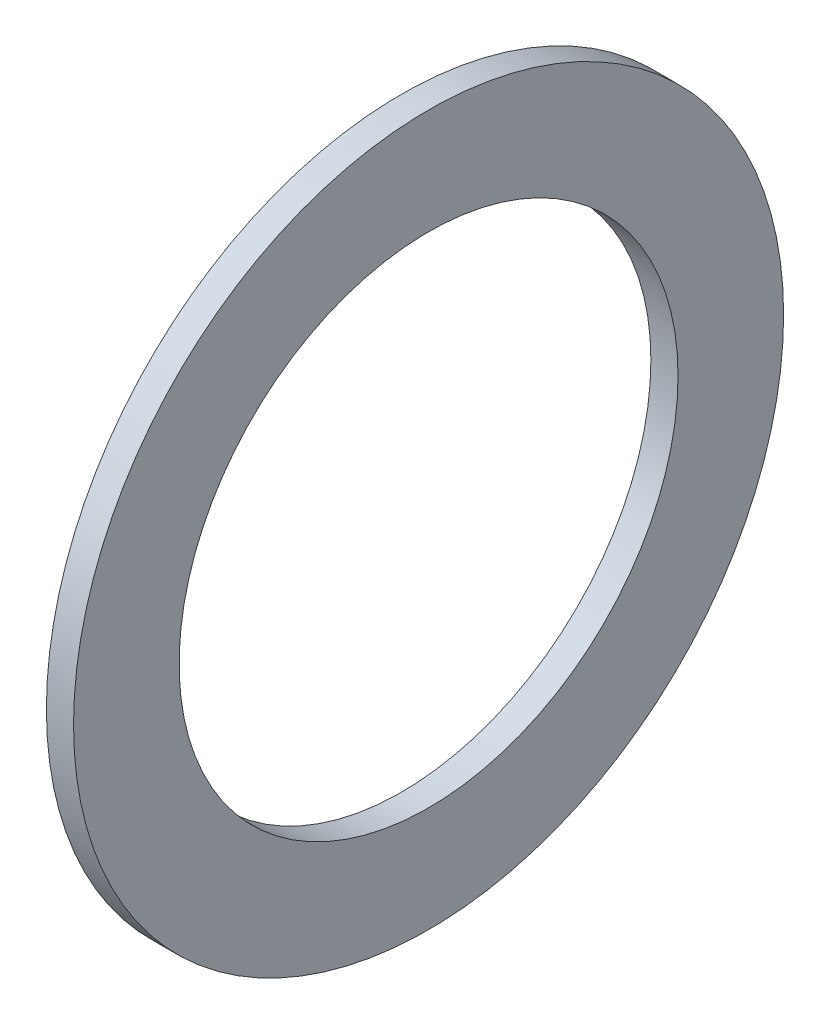
SolidWorks part; units mm, degrees
ref_plane "Front" through (0, 0, 0) normal (0, 0, 1) x (1, 0, 0)
ref_plane "Top" through (0, 0, 0) normal (0, 1, 0) x (1, 0, 0)
ref_plane "Right" through (0, 0, 0) normal (1, 0, 0) x (0, 0, -1)
sketch "Sketch1" plane through (0, 0, 0) normal (1, 0, 0) x (0, 0, -1)
  circle A1 centre (0, 0) radius 17
  circle A2 centre (0, 0) radius 11.945 construction
  circle A3 centre (0, 0) radius 11.945
  dimension "D1" = 5.055
extrude "Boss-Extrude1" add sketch "Sketch1" along normal mid plane 1.3
